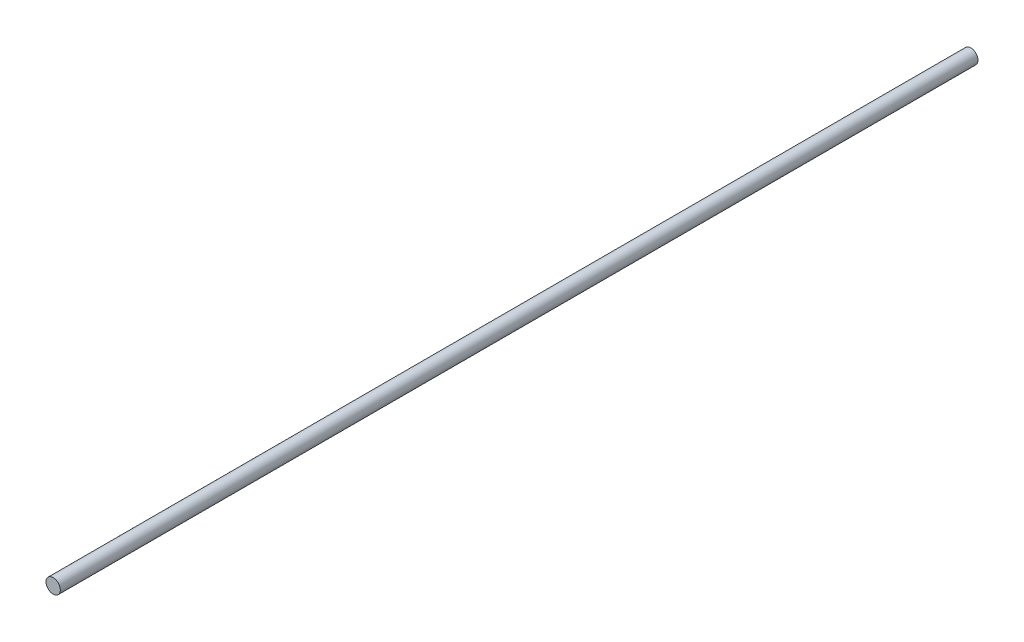
SolidWorks part; units mm, degrees
ref_plane "Front Plane" through (0, 0, 0) normal (0, 0, 1) x (1, 0, 0)
ref_plane "Top Plane" through (0, 0, 0) normal (0, 1, 0) x (1, 0, 0)
ref_plane "Right Plane" through (0, 0, 0) normal (1, 0, 0) x (0, 0, -1)
sketch "Sketch1" plane through (0, 0, 0) normal (0, 0, 1) x (1, 0, 0)
  circle A0 centre (0, 0) radius 1.5875
  dimension "D1" = 3.175
extrude "Boss-Extrude1" add sketch "Sketch1" along normal blind 203.2
